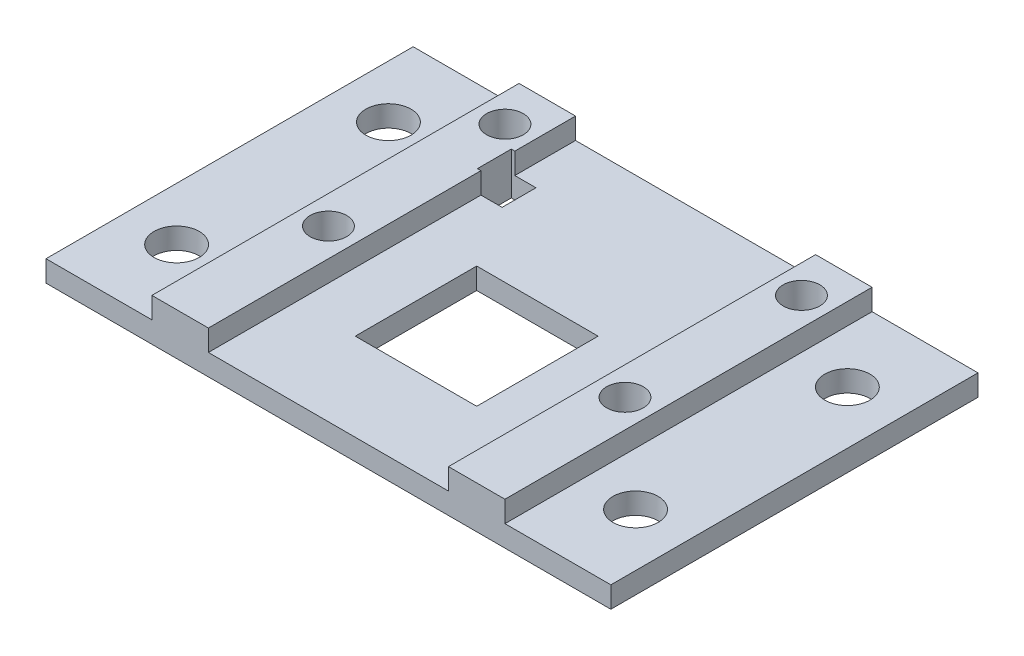
SolidWorks part; units mm, degrees
ref_plane "Front Plane" through (0, 0, 0) normal (0, 0, 1) x (1, 0, 0)
ref_plane "Top Plane" through (0, 0, 0) normal (0, 1, 0) x (1, 0, 0)
ref_plane "Right Plane" through (0, 0, 0) normal (1, 0, 0) x (0, 0, -1)
sketch "camera_ref" plane through (0, 0, 0) normal (0, 1, 0) x (1, 0, 0)
  line L0 (0, 12) -> (0, -12) construction
  line L1 (-12.5, -12) -> (12.5, -12)
  line L2 (-12.5, -12) -> (-12.5, 12)
  line L3 (-12.5, 12) -> (12.5, 12)
  line L4 (12.5, -12) -> (12.5, 12)
  line L5 (-12.5, -12) -> (12.5, 12) construction
  line L6 (-12.5, 12) -> (12.5, -12) construction
  line L8 (-4, -6.5) -> (4, -6.5)
  line L9 (-4, -6.5) -> (-4, 1.5)
  line L10 (-4, 1.5) -> (4, 1.5)
  line L11 (4, -6.5) -> (4, 1.5)
  line L12 (-4, -6.5) -> (4, 1.5) construction
  line L13 (-4, 1.5) -> (4, -6.5) construction
  line L14 (-10.5, -2.5) -> (10.5, -2.5) construction
  line L15 (-10.5, -2.5) -> (-10.5, 10) construction
  line L16 (-10.5, 10) -> (10.5, 10) construction
  line L17 (10.5, -2.5) -> (10.5, 10) construction
  line L18 (-10.5, -2.5) -> (10.5, 10) construction
  line L19 (-10.5, 10) -> (10.5, -2.5) construction
  circle A0 centre (-10.5, 10) radius 1
  circle A1 centre (10.5, 10) radius 1
  circle A2 centre (10.5, -2.5) radius 1
  circle A3 centre (-10.5, -2.5) radius 1
  point P0 (0, 0)
  point P8 (0, -2.5)
  point P13 (0, 3.75)
  dimension "D9" = 2
  dimension "D1" = 24
  dimension "D2" = 25
  dimension "D3" = 8
  dimension "D4" = 8
  dimension "D5" = 5.5
  dimension "D6" = 21
  dimension "D7" = 12.5
  dimension "D8" = 2
sketch "Sketch2" plane through (0, 0, 0) normal (0, 1, 0) x (1, 0, 0)
  line L0 (0, 0) -> (0, 13) construction
  line L1 (-20, -13) -> (20, -13)
  line L2 (-20, -13) -> (-20, 13)
  line L3 (-20, 13) -> (20, 13)
  line L4 (20, -13) -> (20, 13)
  line L5 (0, 0) -> (20, 0) construction
  line L19 (-4.3, -6.8) -> (4.3, -6.8)
  line L20 (4.3, -6.8) -> (4.3, 1.8)
  line L21 (4.3, 1.8) -> (-4.3, 1.8)
  line L22 (-4.3, 1.8) -> (-4.3, -6.8)
  line L23 (-4.3, -6.8) -> (4.3, -6.8)
  line L24 (4.3, -6.8) -> (4.3, 1.8)
  line L25 (4.3, 1.8) -> (-4.3, 1.8)
  line L26 (-4.3, 1.8) -> (-4.3, -6.8)
  circle A0 centre (-10.5, -2.5) radius 1.3
  circle A1 centre (-10.5, 10) radius 1 construction
  circle A2 centre (10.5, 10) radius 1 construction
  circle A3 centre (-10.5, 10) radius 1.3
  circle A4 centre (10.5, -2.5) radius 1 construction
  circle A5 centre (10.5, 10) radius 1.3
  circle A6 centre (10.5, -2.5) radius 1.3
  circle A7 centre (-10.5, -2.5) radius 1 construction
  circle A25 centre (-10.5, -2.5) radius 1 construction
  circle A26 centre (-10.5, 10) radius 1 construction
  circle A27 centre (10.5, 10) radius 1 construction
  circle A28 centre (10.5, -2.5) radius 1 construction
  point P0 (0, 0)
  dimension "D1" = 13
  dimension "D2" = 40
  dimension "D5" = 13
  dimension "D3" = 0.3
  dimension "D4" = 0.3
extrude "Boss-Extrude1" add sketch "Sketch2" along normal blind 1.5
sketch "Sketch3" plane through (0, 1.5, 0) normal (0, 1, 0) x (1, 0, 0)
  line L0 (-10.5, -2.5) -> (-10.5, 10) construction
  line L1 (-12.5, 13) -> (-8.5, 13)
  line L2 (-12.5, 13) -> (-12.5, -13)
  line L3 (-12.5, -13) -> (-8.5, -13)
  line L4 (-8.5, 13) -> (-8.5, -13)
  line L5 (-12.5, 13) -> (-8.5, -13) construction
  line L6 (-12.5, -13) -> (-8.5, 13) construction
  line L7 (-20, -13) -> (20, -13) construction
  line L8 (20, 13) -> (-20, 13) construction
  line L9 (0, 12) -> (0, -12) construction
  line L10 (0, 12) -> (0, -12) construction
  line L11 (12.5, -13) -> (8.5, 13) construction
  line L12 (12.5, 13) -> (8.5, -13) construction
  line L13 (8.5, 13) -> (8.5, -13)
  line L14 (12.5, -13) -> (8.5, -13)
  line L15 (12.5, 13) -> (12.5, -13)
  line L16 (12.5, 13) -> (8.5, 13)
  point P0 (-10.5, 0)
  point P17 (10.5, 0)
  dimension "D1" = 4
extrude "Boss-Extrude2" add sketch "Sketch3" along normal blind 1.5
sketch "Sketch5" plane through (0, 0, 0) normal (0, -1, 0) x (1, 0, 0)
  circle A0 centre (-10.5, 2.5) radius 1.3 construction
  circle A1 centre (10.5, -10) radius 1.3 construction
  circle A2 centre (10.5, 2.5) radius 1.3 construction
  circle A3 centre (-10.5, -10) radius 1.3 construction
  circle A4 centre (-10.5, 2.5) radius 1.3
  circle A5 centre (10.5, -10) radius 1.3
  circle A6 centre (10.5, 2.5) radius 1.3
  circle A7 centre (-10.5, -10) radius 1.3
extrude "Cut-Extrude1" cut sketch "Sketch5" against normal through all
sketch "Sketch6" plane through (0, 1.5, 0) normal (0, 1, 0) x (1, 0, 0)
  line L1 (-8.75, 8.7) -> (-7, 8.7)
  line L2 (-8.75, 8.7) -> (-8.75, 6.3)
  line L3 (-8.75, 6.3) -> (-7, 6.3)
  line L4 (-7, 8.7) -> (-7, 6.3)
  line L6 (-12.5, -12) -> (-12.5, 12) construction
  line L7 (-12.5, 12) -> (12.5, 12) construction
  circle A0 centre (-10.5, 10) radius 1.3 construction
  dimension "D1" = 5.7
  dimension "D2" = 5.5
  dimension "D3" = 1.75
extrude "Cut-Extrude3" cut sketch "Sketch6" against normal through all and the other way through all
sketch "Sketch7" plane through (0, 1.5, 0) normal (0, 1, 0) x (1, 0, 0)
  line L0 (0, 0) -> (0, 7.5) construction
  line L1 (-16.25, -7.5) -> (16.25, -7.5) construction
  line L2 (-16.25, -7.5) -> (-16.25, 7.5) construction
  line L3 (-16.25, 7.5) -> (16.25, 7.5) construction
  line L4 (16.25, -7.5) -> (16.25, 7.5) construction
  line L5 (0, 0) -> (-16.25, 0) construction
  circle A0 centre (16.25, 7.5) radius 1.6
  circle A1 centre (16.25, -7.5) radius 1.6
  circle A2 centre (-16.25, -7.5) radius 1.6
  circle A3 centre (-16.25, 7.5) radius 1.6
  point P0 (0, 0)
  dimension "D1" = 3.2
  dimension "D2" = 32.5
  dimension "D3" = 7.5
  dimension "D4" = 7.5
extrude "Cut-Extrude4" cut sketch "Sketch7" against normal blind 2
